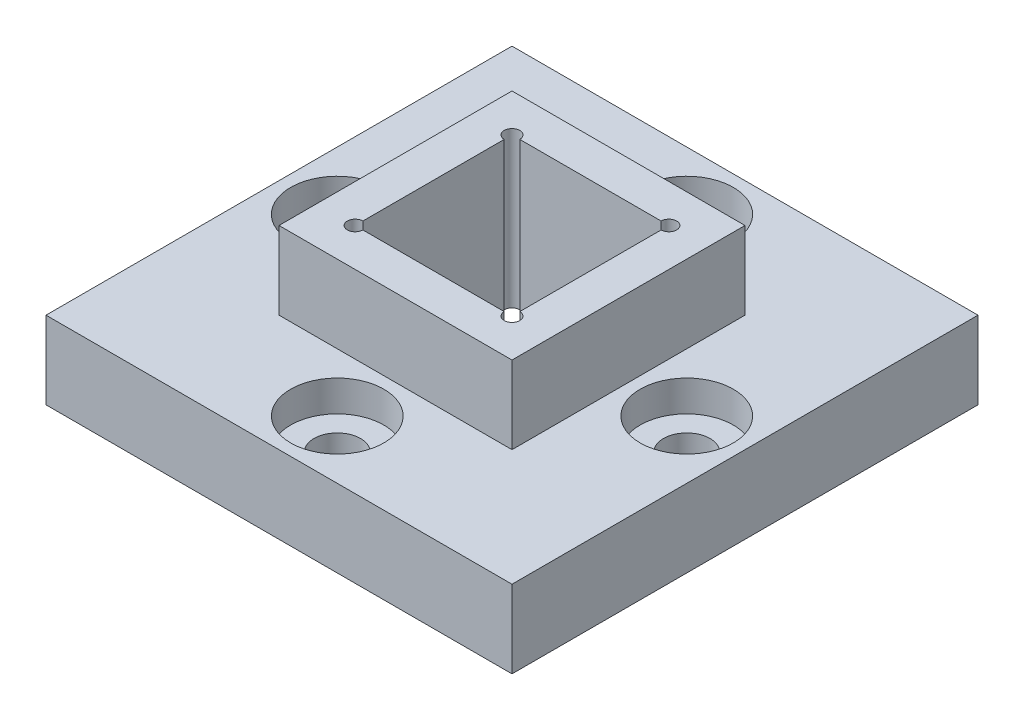
SolidWorks part; units mm, degrees
ref_plane "前视基准面" through (0, 0, 0) normal (0, 0, 1) x (1, 0, 0)
ref_plane "上视基准面" through (0, 0, 0) normal (0, 1, 0) x (1, 0, 0)
ref_plane "右视基准面" through (0, 0, 0) normal (1, 0, 0) x (0, 0, -1)
other "Configuration Table"
sketch "草图1" plane through (0, 0, 0) normal (0, 1, 0) x (1, 0, 0)
  line L1 (-15, 15) -> (15, 15)
  line L2 (-15, 15) -> (-15, -15)
  line L3 (-15, -15) -> (15, -15)
  line L4 (15, 15) -> (15, -15)
  line L5 (-15, 15) -> (15, -15) construction
  line L6 (-15, -15) -> (15, 15) construction
  point P0 (0, 0)
  dimension "D1" = 30
  dimension "D2" = 30
extrude "凸台-拉伸1" add sketch "草图1" along normal blind 5
sketch "草图2" plane through (0, 5, 0) normal (0, 1, 0) x (1, 0, 0)
  line L7 (-7.5, 7.5) -> (7.5, 7.5)
  line L8 (-7.5, 7.5) -> (-7.5, -7.5)
  line L9 (-7.5, -7.5) -> (7.5, -7.5)
  line L10 (7.5, 7.5) -> (7.5, -7.5)
  line L11 (-7.5, 7.5) -> (7.5, -7.5) construction
  line L12 (-7.5, -7.5) -> (7.5, 7.5) construction
  point P0 (0, 0)
  point P1 (0, 0)
  point P6 (0, 0)
  point P11 (0, 0)
  point P12 (12.6357, -6.5349)
  dimension "D2" = 15
extrude "凸台-拉伸2" add sketch "草图2" along normal blind 5
sketch "草图3" plane through (0, 10, 0) normal (0, 1, 0) x (1, 0, 0)
  line L0 (7.5, 0) -> (15, 0) construction
  line L1 (-5.05, 5.05) -> (5.05, 5.05)
  line L2 (-5.05, 5.05) -> (-5.05, -5.05)
  line L3 (-5.05, -5.05) -> (5.05, -5.05)
  line L4 (5.05, 5.05) -> (5.05, -5.05)
  line L5 (-5.05, 5.05) -> (5.05, -5.05) construction
  line L6 (-5.05, -5.05) -> (5.05, 5.05) construction
  line L7 (7.5, -7.5) -> (7.5, 7.5) construction
  line L8 (15, -15) -> (15, 15) construction
  circle A0 centre (-5.05, 5.05) radius 0.5
  circle A1 centre (5.05, 5.05) radius 0.5
  circle A2 centre (-5.05, -5.05) radius 0.5
  circle A3 centre (5.05, -5.05) radius 0.5
  circle A4 centre (11.25, 0) radius 1.5
  circle A5 centre (0, -11.25) radius 1.5
  circle A6 centre (-11.25, 0) radius 1.5
  circle A7 centre (0, 11.25) radius 1.5
  point P0 (0, 0)
  point P19 (2.7356, 11.7889)
  point P20 (0, 0)
  point P26 (0, 0)
  dimension "D2" = 1
  dimension "D3" = 3
  dimension "D1" = 10.1
  dimension "D4" = 4
extrude "切除-拉伸1" cut sketch "草图3" against normal blind 10 contours A3 L4 A1 L1 A0 L2 A2 L3 | L4 A1 L1 | L2 A2 L3 | L3 A2 L2 | L2 A0 L1 | L1 A1 L4 | L4 A3 L3 | A6 | A7 | A4 | A5
sketch "草图4" plane through (0, 5, 0) normal (0, 1, 0) x (1, 0, 0)
  circle A0 centre (11.25, 0) radius 3
  circle A1 centre (0, -11.25) radius 3
  circle A2 centre (-11.25, 0) radius 3
  circle A3 centre (0, 11.25) radius 3
  point P3 (4.0737, 13.3815)
  point P4 (0, 0)
  point P12 (0, 0)
  dimension "D1" = 6
  dimension "D2" = 4
extrude "切除-拉伸2" cut sketch "草图4" against normal blind 2
